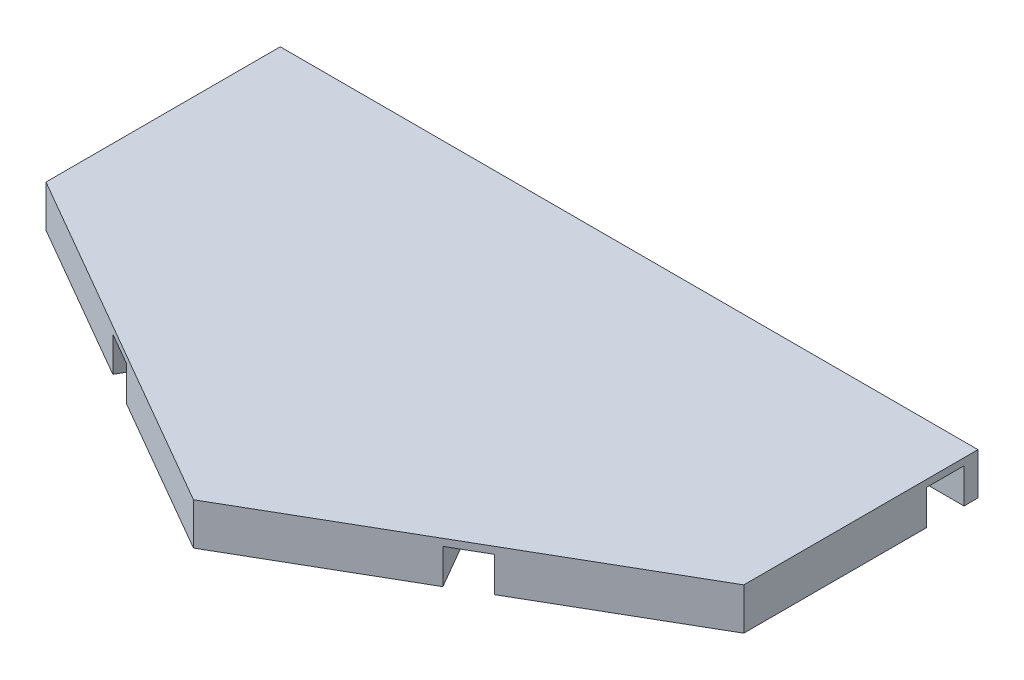
SolidWorks part; units mm, degrees
material "PET"
ref_plane "Front Plane" through (0, 0, 0) normal (0, 0, 1) x (1, 0, 0)
ref_plane "Top Plane" through (0, 0, 0) normal (0, 1, 0) x (1, 0, 0)
ref_plane "Right Plane" through (0, 0, 0) normal (1, 0, 0) x (0, 0, -1)
sketch "Sketch1" plane through (0, 0, 0) normal (0, 1, 0) x (1, 0, 0)
  line L0 (25, 43.3013) -> (-25, -43.3013) construction
  line L1 (0, 57.735) -> (-50, 28.8675)
  line L2 (-50, 28.8675) -> (-50, -28.8675)
  line L3 (-50, -28.8675) -> (0, -57.735)
  line L4 (0, -57.735) -> (50, -28.8675)
  line L5 (50, -28.8675) -> (50, 28.8675)
  line L6 (50, 28.8675) -> (0, 57.735)
  circle A0 centre (0, 0) radius 50 construction
  dimension "D2" = 100
extrude "Boss-Extrude1" add sketch "Sketch1" along normal blind 6
sketch "Sketch2" plane through (0, 0, 0) normal (0, -1, 0) x (1, 0, 0)
  line L0 (-25, 43.3013) -> (-1, 1.7321)
  line L3 (-50, 28.8675) -> (0, 57.735) construction
  line L6 (50, 0) -> (-50, 0)
  line L7 (50, 28.8675) -> (50, -28.8675) construction
  line L8 (-50, -28.8675) -> (-50, 28.8675) construction
  line L9 (0, 0) -> (0, -57.735) construction
  line L10 (25, 43.3013) -> (1, 1.7321)
  point P4 (0, 0)
  dimension "D1" = 2
extrude "Cut-Extrude-Thin1" cut sketch "Sketch2" against normal blind 5 thin thin type mid plane wall 5.4
sketch "Sketch3" plane through (0, 0, 0) normal (0, -1, 0) x (1, 0, 0)
  line L3 (-50, 28.8675) -> (0, 57.735)
  line L4 (0, 57.735) -> (50, 28.8675)
  line L5 (-50, 28.8675) -> (-50, -4.7)
  line L6 (-50, -28.8675) -> (-50, -2.7) construction
  line L7 (-50, -4.7) -> (50, -4.7)
  line L8 (50, -2.7) -> (50, -28.8675) construction
  line L9 (50, -4.7) -> (50, 28.8675)
  line L11 (50, -2.7) -> (-50, -2.7) construction
  dimension "D1" = 2
extrude "Cut-Extrude1" cut sketch "Sketch3" against normal up to surface (6 mm away) flip side to cut up to face at (0, 6, 0)
